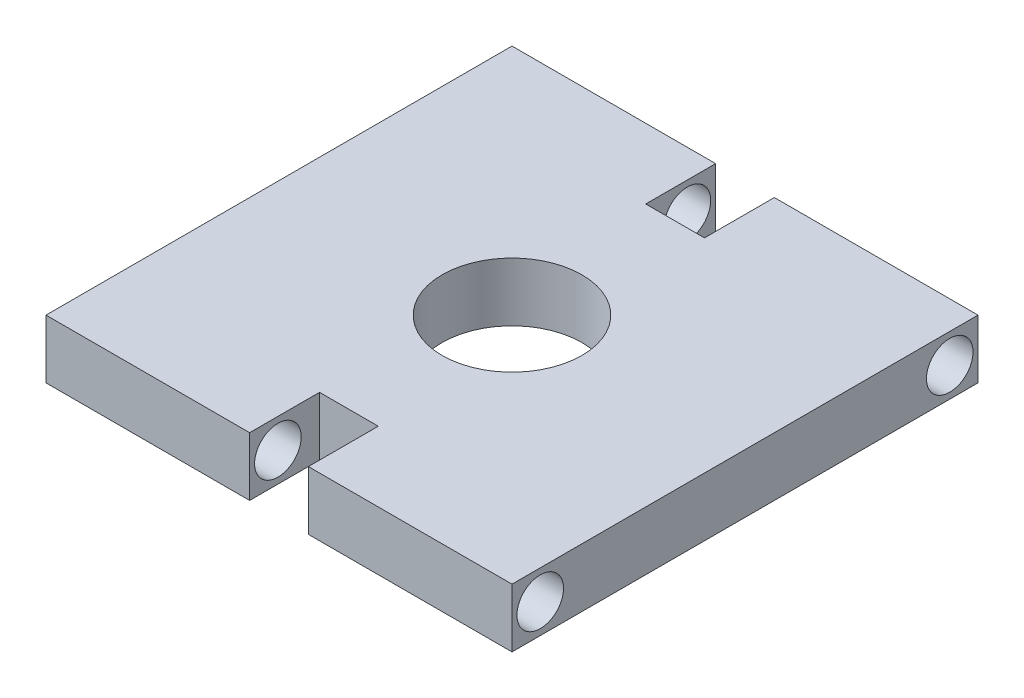
SolidWorks part; units mm, degrees
ref_plane "Front Plane" through (0, 0, 0) normal (0, 0, 1) x (1, 0, 0)
ref_plane "Top Plane" through (0, 0, 0) normal (0, 1, 0) x (1, 0, 0)
ref_plane "Right Plane" through (0, 0, 0) normal (1, 0, 0) x (0, 0, -1)
sketch "Sketch1" plane through (0, 0, 0) normal (0, 1, 0) x (1, 0, 0)
  line L0 (0, 25.4) -> (11.0998, 25.4)
  line L1 (14.3002, 0) -> (25.4, 0)
  line L2 (0, 0) -> (0, 25.4)
  line L3 (14.3002, 25.4) -> (25.4, 25.4)
  line L4 (25.4, 0) -> (25.4, 25.4)
  line L5 (0, 12.7) -> (25.4, 12.7) construction
  line L6 (11.0998, 25.4) -> (11.0998, 21.59)
  line L7 (11.0998, 21.59) -> (14.3002, 21.59)
  line L8 (14.3002, 25.4) -> (14.3002, 21.59)
  line L9 (12.7, 12.7) -> (12.7, 25.4) construction
  line L10 (14.3002, 0) -> (14.3002, 3.81)
  line L11 (11.0998, 3.81) -> (14.3002, 3.81)
  line L12 (11.0998, 0) -> (11.0998, 3.81)
  line L13 (0, 0) -> (11.0998, 0)
  circle A0 centre (12.7, 12.7) radius 3.81
  point P0 (0, 0)
  dimension "D5" = 7.62
  dimension "D1" = 3.2004
  dimension "D2" = 12.7
  dimension "D3" = 12.7
  dimension "D4" = 3.81
extrude "Boss-Extrude1" add sketch "Sketch1" along normal blind 3.2004
sketch "Sketch3" plane through (25.4, 0, 0) normal (1, 0, 0) x (0, 0, -1)
  line L0 (25.4, 1.6002) -> (0, 1.6002) construction
  line L3 (25.4, 3.2004) -> (25.4, 0) construction
  line L6 (0, 3.2004) -> (0, 0) construction
  line L7 (12.7, 3.2004) -> (12.7, 0) construction
  line L8 (0, 3.2004) -> (25.4, 3.2004) construction
  line L9 (0, 0) -> (25.4, 0) construction
  circle A0 centre (23.8602, 1.6002) radius 1.27
  circle A1 centre (1.5398, 1.6002) radius 1.27
  dimension "D1" = 2.54
extrude "Cut-Extrude2" cut sketch "Sketch3" against normal through all contours A0 | A1
